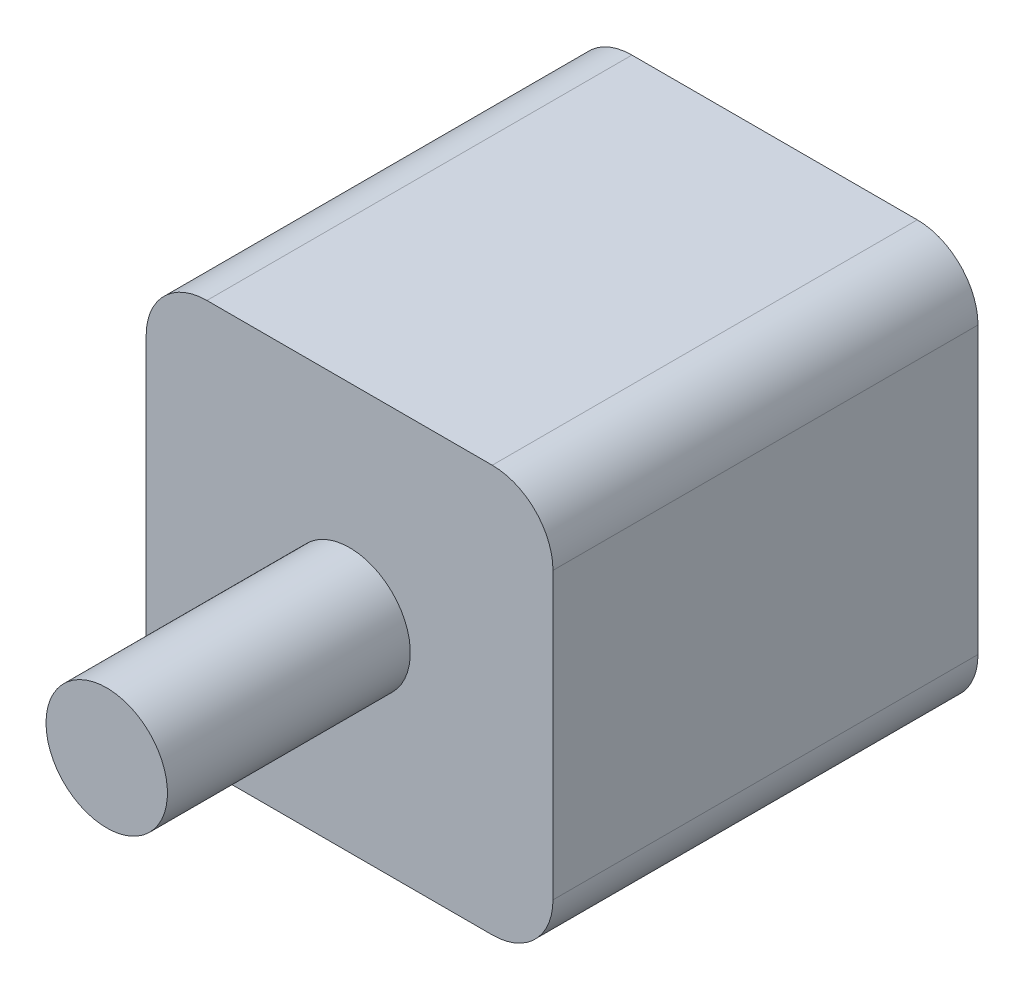
SolidWorks part; units mm, degrees
ref_plane "Front Plane" through (0, 0, 0) normal (0, 0, 1) x (1, 0, 0)
ref_plane "Top Plane" through (0, 0, 0) normal (0, 1, 0) x (1, 0, 0)
ref_plane "Right Plane" through (0, 0, 0) normal (1, 0, 0) x (0, 0, -1)
sketch "Sketch1" plane through (0, 0, 0) normal (0, 0, 1) x (1, 0, 0)
  line L1 (0, 0) -> (42.545, 0)
  line L2 (0, 0) -> (0, 42.545)
  line L3 (0, 42.545) -> (42.545, 42.545)
  line L4 (42.545, 0) -> (42.545, 42.545)
  dimension "D1" = 42.545
  dimension "D2" = 42.545
extrude "Boss-Extrude1" add sketch "Sketch1" along normal blind 44.45
fillet "Fillet2" radius 6.35 4 edges at (0, 0, 22.225) (42.545, 0, 22.225) (42.545, 42.545, 22.225) (0, 42.545, 22.225)
sketch "Sketch2" plane through (0, 0, 0) normal (0, 0, -1) x (-1, 0, 0)
  line L0 (-21.2725, 42.545) -> (-21.2725, 0) construction
  line L1 (-36.195, 42.545) -> (-6.35, 42.545) construction
  line L2 (-6.35, 0) -> (-36.195, 0) construction
  line L4 (0, 36.195) -> (0, 6.35) construction
  line L5 (0, 21.2725) -> (-42.545, 21.2725) construction
  line L6 (-42.545, 6.35) -> (-42.545, 36.195) construction
  circle A0 centre (-21.2725, 21.2725) radius 6.35
extrude "Boss-Extrude2" add sketch "Sketch2" against normal blind 69.85
